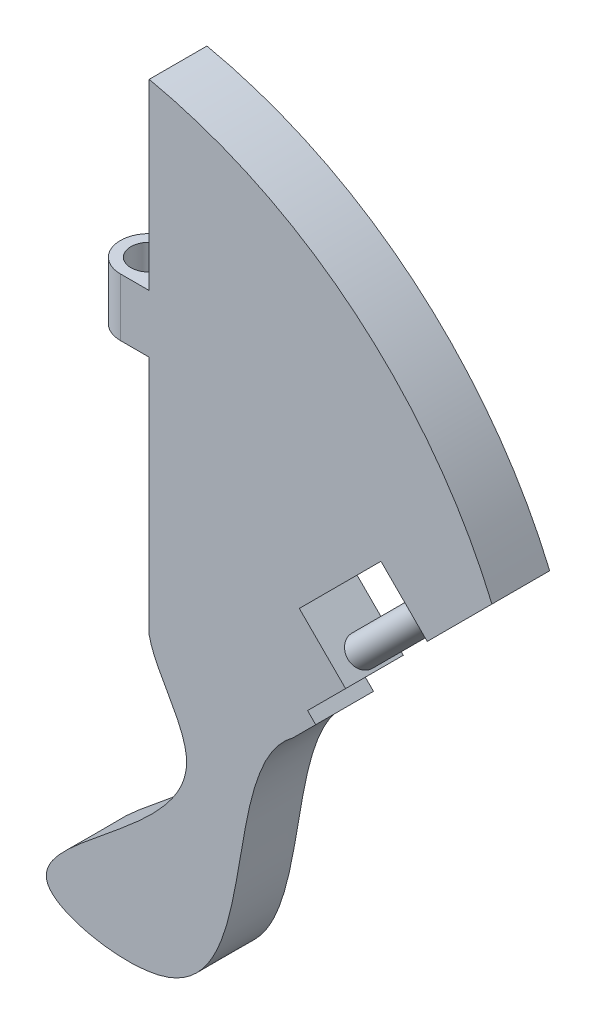
SolidWorks part; units mm, degrees
ref_plane "Alzado" through (0, 0, 0) normal (0, 0, 1) x (1, 0, 0)
ref_plane "Planta" through (0, 0, 0) normal (0, 1, 0) x (1, 0, 0)
ref_plane "Vista lateral" through (0, 0, 0) normal (1, 0, 0) x (0, 0, -1)
sketch "Croquis1" plane through (0, 0, 0) normal (0, 0, 1) x (1, 0, 0)
  line L0 (0, 0) -> (0, 50)
  line L1 (14.888, -1.8298) -> (36.1012, 19.3834)
  arc A0 (0, 50) -> (36.1012, 19.3834) centre (-10.4366, 1.1014) cw
  spline S0 degree 3 poles (0, 0) (0.6235, -3.0112) (11.2925, -13.692) (-21.6004, -27.4888) (13.9906, -34.4153) (6.9905, -7.6154) (14.888, -1.8298) knots 0 0 0 0 0.133846 0.436861 0.593183 1 1 1 1
  dimension "D4" = 50
  dimension "D1" = 50
  dimension "D2" = 30
  dimension "D3" = 30
  dimension "D5" = 45
  dimension "D6" = 15
extrude "Saliente-Extruir1" add sketch "Croquis1" along normal blind 6
sketch "Croquis2" plane through (0, 0, 0) normal (0, 1, 0) x (1, 0, 0)
  line L0 (-10.6894, -6) -> (14.888, -6) construction
  line L1 (0, 0) -> (-3, 0)
  line L2 (0, 0) -> (0, -6)
  line L3 (0, -6) -> (-3, -6)
  arc A0 (-3, 0) -> (-3, -6) centre (-3, -3) ccw
  dimension "D1" = 3
extrude "Saliente-Extruir2" add sketch "Croquis2" along normal blind 6 from offset 25
sketch "Croquis3" plane through (0, 31, 0) normal (0, 1, 0) x (1, 0, 0)
  circle A0 centre (-3, -3) radius 1.9
  dimension "D1" = 3.8
extrude "Cortar-Extruir1" cut sketch "Croquis3" against normal blind 6
sketch "Croquis4" plane through (0, 0, 0) normal (0, 0, -1) x (-1, 0, 0)
  line L0 (-29.7372, 13.0194) -> (-24.0804, 18.6763)
  line L1 (-14.888, -1.8298) -> (-36.1012, 19.3834) construction
  line L2 (-24.0804, 18.6763) -> (-15.5951, 10.191)
  line L3 (-15.5951, 10.191) -> (-21.2519, 4.5341)
  line L4 (-29.7372, 13.0194) -> (-21.2519, 4.5341)
  dimension "D1" = 12
  dimension "D2" = 8
  dimension "D3" = 9
extrude "Cortar-Extruir3" cut sketch "Croquis4" against normal blind 6
sketch "Croquis5" plane through (12.893, 12.893, 0) normal (0.7071, 0.7071, 0) x (0, 0, -1)
  line L0 (-6, -11.8213) -> (0, -11.8213) construction
  line L1 (0, -11.8213) -> (0, -3.8213) construction
  circle A0 centre (-3, -8.8213) radius 1.5
  dimension "D1" = 3
  dimension "D2" = 3
  dimension "D3" = 3
extrude "Saliente-Extruir3" add sketch "Croquis5" along normal up to next
sketch "Croquis6" plane through (0, 0, 6) normal (0, 0, 1) x (1, 0, 0)
  line L0 (36.1012, 19.3834) -> (17.3027, 0.585)
  line L1 (14.888, -1.8298) -> (21.2519, 4.5341) construction
  line L2 (17.3027, 0.585) -> (16.4542, 1.4335)
  line L3 (16.4542, 1.4335) -> (35.6095, 20.5887)
  line L4 (35.6095, 20.5887) -> (36.1012, 19.3834)
  arc A0 (36.1012, 19.3834) -> (0, 50) centre (-10.4366, 1.1014) ccw construction
  dimension "D1" = 1.2
extrude "Cortar-Extruir4" cut sketch "Croquis6" against normal blind 10
